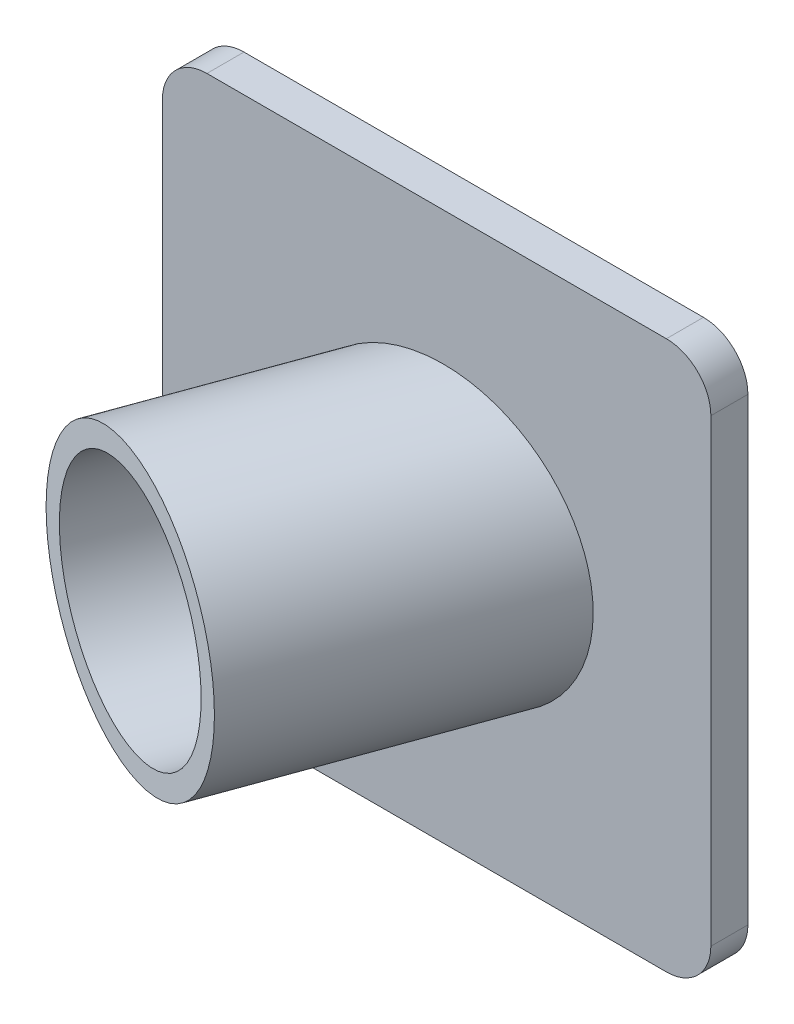
SolidWorks part; units mm, degrees
ref_plane "前基準面" through (0, 0, 0) normal (0, 0, 1) x (1, 0, 0)
ref_plane "上基準面" through (0, 0, 0) normal (0, 1, 0) x (1, 0, 0)
ref_plane "右基準面" through (0, 0, 0) normal (1, 0, 0) x (0, 0, -1)
sketch "草圖1" plane through (0, 0, 0) normal (0, 0, 1) x (1, 0, 0)
  line L1 (-15.5, -18.5) -> (15.5, -18.5)
  line L2 (-18.5, -15.5) -> (-18.5, 15.5)
  line L3 (-15.5, 18.5) -> (15.5, 18.5)
  line L4 (18.5, -15.5) -> (18.5, 15.5)
  line L5 (-18.5, -18.5) -> (18.5, 18.5) construction
  line L6 (-18.5, 18.5) -> (18.5, -18.5) construction
  arc A2 (-18.5, 15.5) -> (-15.5, 18.5) centre (-15.5, 15.5) cw
  arc A3 (-15.5, -18.5) -> (-18.5, -15.5) centre (-15.5, -15.5) cw
  arc A4 (15.5, -18.5) -> (18.5, -15.5) centre (15.5, -15.5) ccw
  arc A5 (18.5, 15.5) -> (15.5, 18.5) centre (15.5, 15.5) ccw
  point P0 (0, 0)
  point P19 (0, 0)
  dimension "D1" = 37
  dimension "D3" = 3
  dimension "D4" = 3
  dimension "D2" = 37
extrude "填料-伸長1" add sketch "草圖1" along normal blind 2.5
ref_plane "平面1" through (-2.9676, 0, 8.1533) normal (-0.342, 0, 0.9397) x (0, -1, 0)
sketch "草圖4" plane through (0, 0, 0) normal (0, 1, 0) x (1, 0, 0)
  line L0 (0, -2.5) -> (-7.9771, -24.4168) construction
  line L1 (15.5, -2.5) -> (-15.5, -2.5) construction
  line L2 (-23.6408, -0.6289) -> (17.7057, -15.6778) construction
sketch "草圖6" plane through (-2.9676, 0, 8.1533) normal (-0.342, 0, 0.9397) x (0, -1, 0)
  circle A1 centre (0, 1.2803) radius 7.5
  circle A2 centre (0, 1.2803) radius 9.5
  point P0 (0, 1.2803)
  dimension "D1" = 2
extrude "填料-伸長3" add sketch "草圖6" against normal up to surface (9.9399 mm away) contours A2
sketch "草圖9" plane through (-2.9676, 0, 8.1533) normal (-0.342, 0, 0.9397) x (0.9397, 0, 0.342)
  circle A0 centre (1.2903, 0) radius 8
  point P0 (1.2903, 0)
  dimension "D1" = 16
sketch "草圖12" plane through (-2.9676, 0, 8.1533) normal (-0.342, 0, 0.9397) x (0.9397, 0, 0.342)
  circle A0 centre (1.2803, 0) radius 9.5
extrude "填料-伸長4" add sketch "草圖12" along normal blind 10
sketch "草圖13" plane through (-6.3878, 0, 17.5503) normal (-0.342, 0, 0.9397) x (0.9397, 0, 0.342)
  circle A2 centre (1.2803, 0) radius 8
  dimension "D1" = 16
extrude "除料-伸長4" cut sketch "草圖13" along direction (-0.342, 0, 0.9397) on the side against the normal up to surface (19.3939 mm away)
